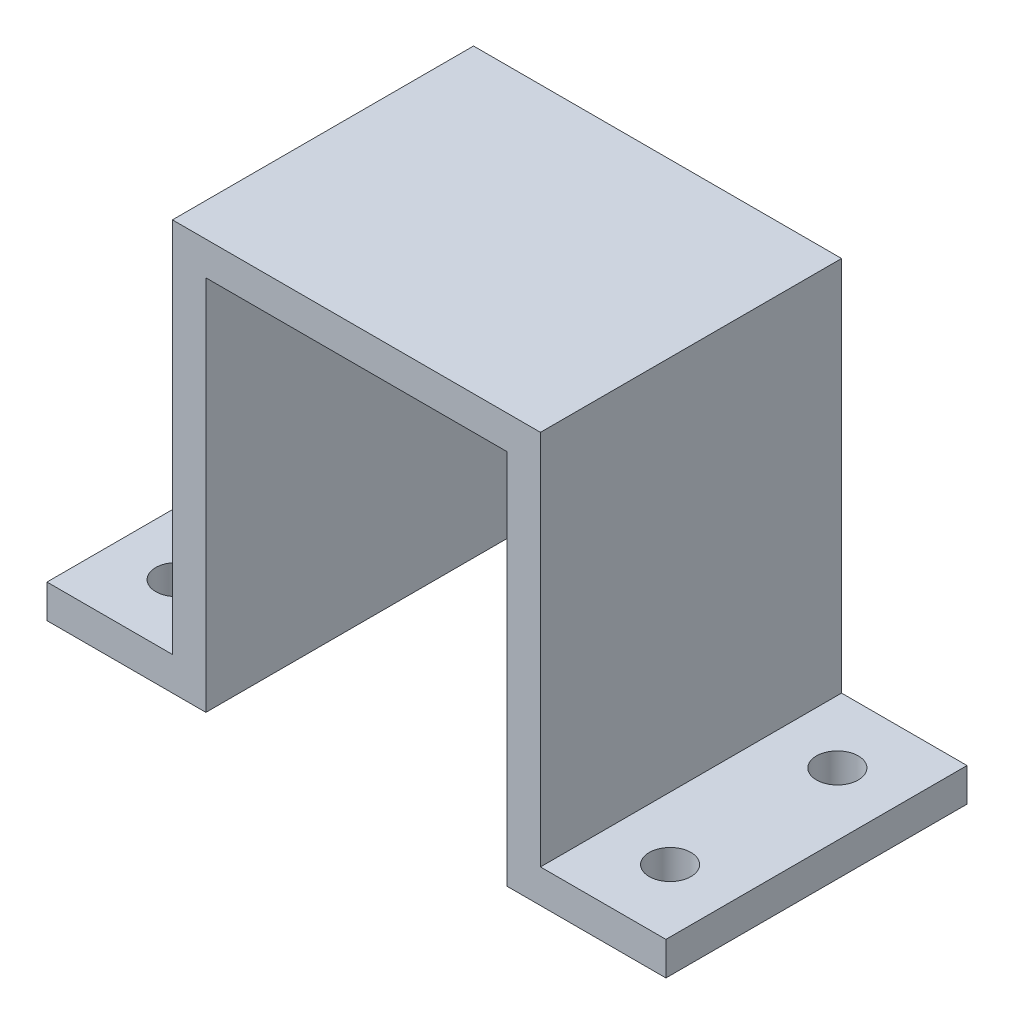
SolidWorks part; units mm, degrees
ref_plane "前视基准面" through (0, 0, 0) normal (0, 0, 1) x (1, 0, 0)
ref_plane "上视基准面" through (0, 0, 0) normal (0, 1, 0) x (1, 0, 0)
ref_plane "右视基准面" through (0, 0, 0) normal (1, 0, 0) x (0, 0, -1)
sketch "草图1" plane through (0, 0, 0) normal (0, 0, 1) x (1, 0, 0)
  line L0 (-4, 0) -> (0, 0)
  line L1 (0, 0) -> (36, 0)
  line L3 (0, -4) -> (36, -4)
  line L5 (36, 0) -> (40, 0)
  line L6 (36, -4) -> (36, -49)
  line L7 (36, -49) -> (40, -49)
  line L8 (40, 0) -> (40, -45)
  line L9 (40, -49) -> (55, -49)
  line L11 (40, -45) -> (55, -45)
  line L12 (55, -49) -> (55, -45)
  line L13 (-19, -49) -> (-19, -45)
  line L14 (-4, -45) -> (-19, -45)
  line L16 (-4, -49) -> (-19, -49)
  line L17 (-4, 0) -> (-4, -45)
  line L18 (0, -49) -> (-4, -49)
  line L19 (0, -4) -> (0, -49)
  dimension "D1" = 49
extrude "凸台-拉伸1" add sketch "草图1" along normal blind 36
sketch "草图2" plane through (0, -45, 0) normal (0, 1, 0) x (1, 0, 0)
  line L7 (40, 0) -> (-4, 0) construction
  line L8 (18, 0) -> (18, -36)
  line L9 (40, -36) -> (-4, -36) construction
  circle A0 centre (-11.5, -8) radius 2.5
  circle A1 centre (-11.5, -28) radius 2.5
  circle A2 centre (47.5, -28) radius 2.5
  circle A3 centre (47.5, -8) radius 2.5
extrude "切除-拉伸1" cut sketch "草图2" against normal blind 36 contours A0 | A1 | A2 | A3
